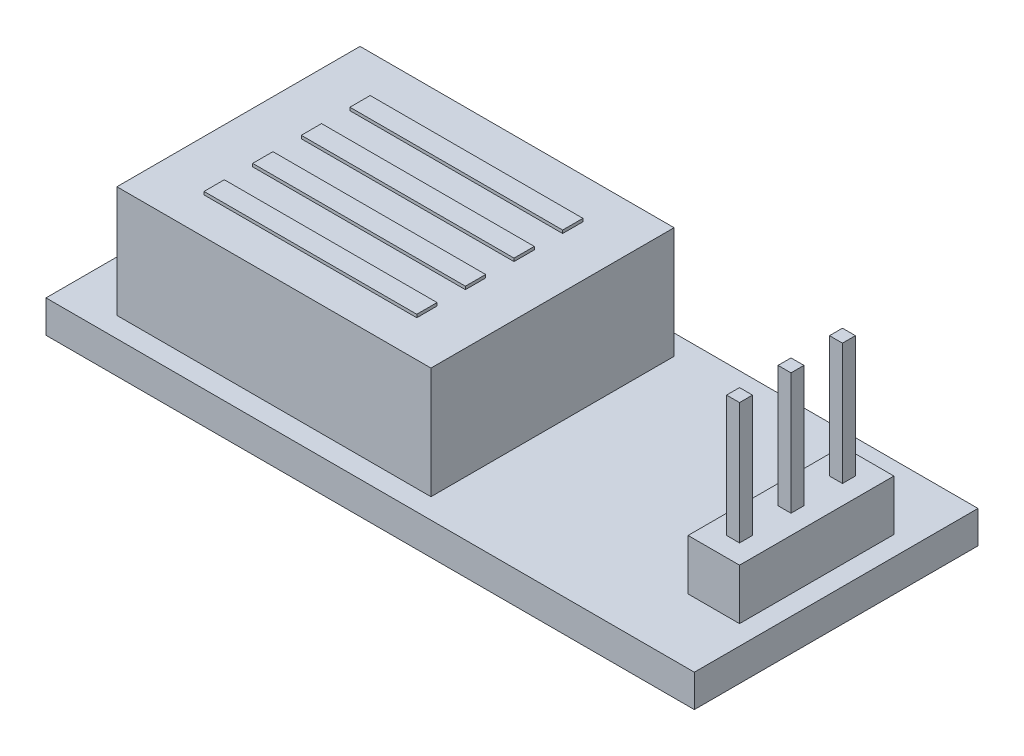
SolidWorks part; units mm, degrees
ref_plane "Front Plane" through (0, 0, 0) normal (0, 0, 1) x (1, 0, 0)
ref_plane "Top Plane" through (0, 0, 0) normal (0, 1, 0) x (1, 0, 0)
ref_plane "Right Plane" through (0, 0, 0) normal (1, 0, 0) x (0, 0, -1)
sketch "SK PCB" plane through (0, 0, 0) normal (0, 1, 0) x (1, 0, 0)
  line L1 (0, 14) -> (32, 14)
  line L2 (0, 14) -> (0, 0)
  line L3 (0, 0) -> (32, 0)
  line L4 (32, 14) -> (32, 0)
extrude "PCB" add sketch "SK PCB" along normal blind 1.6 separate body
sketch "SK DHT11 housing" plane through (0, 0, 0) normal (0, 1, 0) x (1, 0, 0)
  line L1 (2.5, 13) -> (18, 13)
  line L2 (2.5, 13) -> (2.5, 1)
  line L3 (2.5, 1) -> (18, 1)
  line L4 (18, 13) -> (18, 1)
extrude "DHT11 housing" add sketch "SK DHT11 housing" along normal blind 5.5 from offset 1.6 separate body
sketch "SK Grille" plane through (0, 0, 0) normal (0, 1, 0) x (1, 0, 0)
  line L1 (5, 11) -> (15.5, 11)
  line L2 (5, 11) -> (5, 10)
  line L3 (5, 10) -> (15.5, 10)
  line L4 (15.5, 11) -> (15.5, 10)
  line L6 (5, 8.6) -> (15.5, 8.6)
  line L7 (5, 8.6) -> (5, 7.6)
  line L8 (5, 7.6) -> (15.5, 7.6)
  line L9 (15.5, 8.6) -> (15.5, 7.6)
  line L11 (5, 6.2) -> (15.5, 6.2)
  line L12 (5, 6.2) -> (5, 5.2)
  line L13 (5, 5.2) -> (15.5, 5.2)
  line L14 (15.5, 6.2) -> (15.5, 5.2)
  line L16 (5, 3.8) -> (15.5, 3.8)
  line L17 (5, 3.8) -> (5, 2.8)
  line L18 (5, 2.8) -> (15.5, 2.8)
  line L19 (15.5, 3.8) -> (15.5, 2.8)
extrude "Grille" add sketch "SK Grille" along normal blind 0.15 from offset 7.1 separate body
sketch "SK Header 3 pin" plane through (0, 0, 0) normal (0, 1, 0) x (1, 0, 0)
  line L1 (28.5, 10.81) -> (31.04, 10.81)
  line L2 (28.5, 10.81) -> (28.5, 3.19)
  line L3 (28.5, 3.19) -> (31.04, 3.19)
  line L4 (31.04, 10.81) -> (31.04, 3.19)
extrude "Header 3 pin" add sketch "SK Header 3 pin" along normal blind 2.5 from offset 1.6 separate body
sketch "SK Header pins" plane through (0, 0, 0) normal (0, 1, 0) x (1, 0, 0)
  line L1 (29.45, 9.86) -> (30.09, 9.86)
  line L2 (29.45, 9.86) -> (29.45, 9.22)
  line L3 (29.45, 9.22) -> (30.09, 9.22)
  line L4 (30.09, 9.86) -> (30.09, 9.22)
  line L6 (29.45, 7.32) -> (30.09, 7.32)
  line L7 (29.45, 7.32) -> (29.45, 6.68)
  line L8 (29.45, 6.68) -> (30.09, 6.68)
  line L9 (30.09, 7.32) -> (30.09, 6.68)
  line L11 (29.45, 4.78) -> (30.09, 4.78)
  line L12 (29.45, 4.78) -> (29.45, 4.14)
  line L13 (29.45, 4.14) -> (30.09, 4.14)
  line L14 (30.09, 4.78) -> (30.09, 4.14)
extrude "Header pins" add sketch "SK Header pins" along normal blind 6 from offset 4.1 separate body
